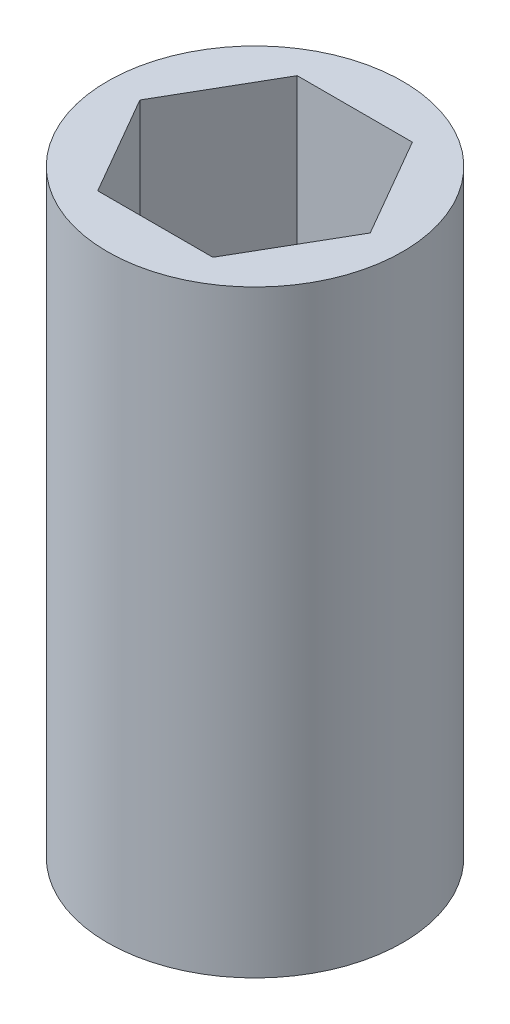
SolidWorks part; units mm, degrees
ref_plane "Front Plane" through (0, 0, 0) normal (0, 0, 1) x (1, 0, 0)
ref_plane "Top Plane" through (0, 0, 0) normal (0, 1, 0) x (1, 0, 0)
ref_plane "Right Plane" through (0, 0, 0) normal (1, 0, 0) x (0, 0, -1)
sketch "Sketch1" plane through (0, 0, 0) normal (0, 1, 0) x (1, 0, 0)
  line L1 (2.7863, -4.826) -> (5.5726, 0)
  line L2 (5.5726, 0) -> (2.7863, 4.826)
  line L3 (2.7863, 4.826) -> (-2.7863, 4.826)
  line L4 (-2.7863, 4.826) -> (-5.5726, 0)
  line L5 (-5.5726, 0) -> (-2.7863, -4.826)
  line L6 (-2.7863, -4.826) -> (2.7863, -4.826)
  circle A0 centre (0, 0) radius 7.1438
  circle A1 centre (0, 0) radius 4.826 construction
  dimension "D1" = 9.652
  dimension "D2" = 14.2875
extrude "Boss-Extrude1" add sketch "Sketch1" along normal mid plane 28.956
